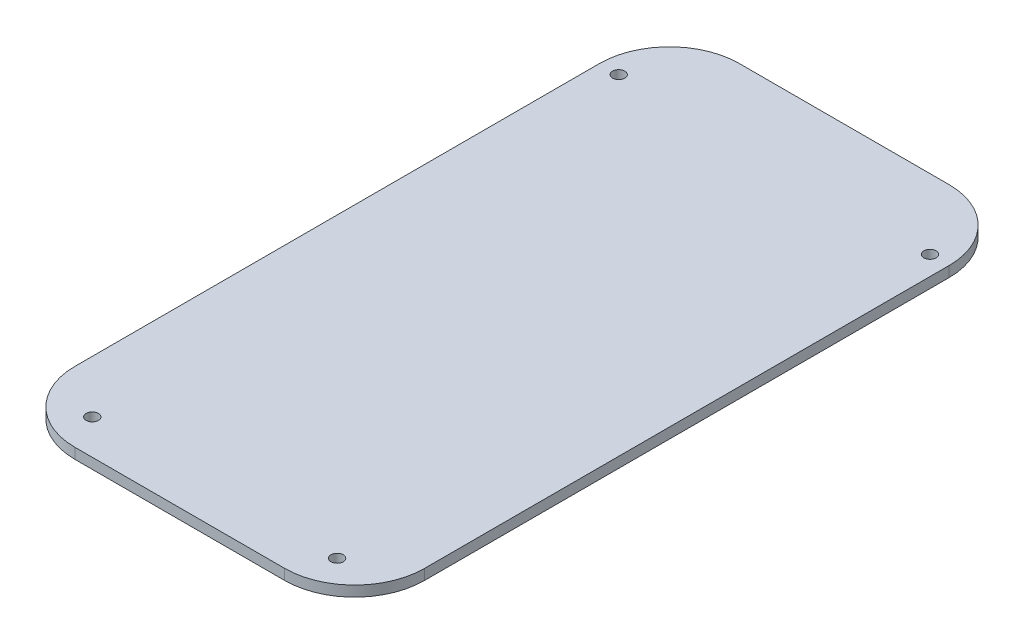
SolidWorks part; units mm, degrees
ref_plane "Front Plane" through (0, 0, 0) normal (0, 0, 1) x (1, 0, 0)
ref_plane "Top Plane" through (0, 0, 0) normal (0, 1, 0) x (1, 0, 0)
ref_plane "Right Plane" through (0, 0, 0) normal (1, 0, 0) x (0, 0, -1)
sketch "Sketch1" plane through (0, 0, 0) normal (0, 1, 0) x (1, 0, 0)
  line L0 (50, 190) -> (50, 0) construction
  line L1 (20, 0) -> (80, 0)
  line L2 (0, 20) -> (0, 170)
  line L3 (20, 190) -> (80, 190)
  line L5 (100, 20) -> (100, 170)
  circle A1 centre (5.5, 170) radius 1.75
  circle A2 centre (15, 10) radius 1.75
  arc A4 (20, 0) -> (0, 20) centre (20, 20) cw
  arc A5 (0, 170) -> (20, 190) centre (20, 170) cw
  circle A6 centre (85, 10) radius 1.75
  circle A7 centre (94.5, 170) radius 1.75
  arc A8 (80, 0) -> (100, 20) centre (80, 20) ccw
  arc A9 (100, 170) -> (80, 190) centre (80, 170) ccw
  point P5 (0, 0)
  point P12 (0, 190)
  dimension "D3" = 44.5
  dimension "D4" = 35
  dimension "D5" = 3.5
  dimension "D6" = 20
  dimension "D7" = 20
  dimension "D8" = 10
  dimension "D1" = 50
  dimension "D2" = 190
extrude "Boss-Extrude1" add sketch "Sketch1" along normal blind 3
